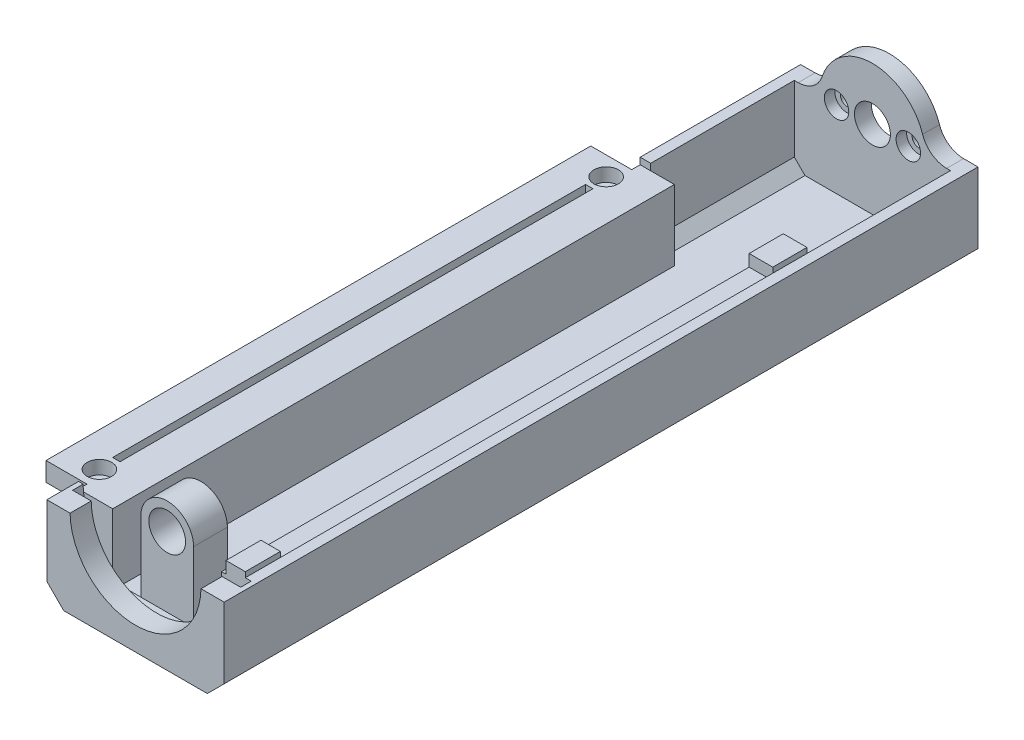
SolidWorks part; units mm, degrees
ref_plane "Front Plane" through (0, 0, 0) normal (0, 0, 1) x (1, 0, 0)
ref_plane "Top Plane" through (0, 0, 0) normal (0, 1, 0) x (1, 0, 0)
ref_plane "Right Plane" through (0, 0, 0) normal (1, 0, 0) x (0, 0, -1)
sketch "Sketch1" plane through (0, 0, 0) normal (0, 0, 1) x (1, 0, 0)
  line L0 (-21, -0.25) -> (21, -0.25)
  line L1 (-21, 21) -> (21, 21) construction
  line L2 (-21, 21) -> (-21, -21) construction
  line L3 (-21, -21) -> (21, -21) construction
  line L4 (21, 21) -> (21, -21) construction
  line L5 (-21, 21) -> (21, -21) construction
  line L6 (-21, -21) -> (21, 21) construction
  line L7 (21, -0.25) -> (21, -17)
  line L8 (21, -17) -> (17, -21)
  line L9 (17, -21) -> (-17, -21)
  line L10 (-17, -21) -> (-21, -17)
  line L11 (-21, -17) -> (-21, -0.25)
  point P0 (0, 0)
  dimension "D1" = 42
  dimension "D2" = 0.25
  dimension "D3" = 4
  dimension "D4" = 4
  dimension "D5" = 4
extrude "Boss-Extrude1" add sketch "Sketch1" along normal blind 178.5 contours L11 L0 L7 L8 L9 L10
ref_plane "Plane1" through (0, 0, 173.5) normal (0, 0, 1) x (1, 0, 0)
sketch "Sketch4" plane through (0, 0, 173.5) normal (0, 0, 1) x (1, 0, 0)
  line L6 (-18.5, -15.9645) -> (-15.9645, -18.5)
  line L7 (-15.9645, -18.5) -> (15.9645, -18.5)
  line L8 (15.9645, -18.5) -> (18.5, -15.9645)
  line L9 (18.5, -15.9645) -> (18.5, -2.75)
  line L11 (-18.5, -2.75) -> (-18.5, -15.9645)
  line L18 (-21, -17) -> (-17, -21)
  line L22 (-21, -0.25) -> (-21, -17)
  line L23 (21, -0.25) -> (-21, -0.25)
  line L24 (21, -17) -> (21, -0.25)
  line L25 (17, -21) -> (21, -17)
  line L26 (-17, -21) -> (17, -21)
  line L27 (-21, -17) -> (-17, -21) construction
  line L28 (-21, -0.25) -> (-21, -17) construction
  line L29 (21, -0.25) -> (-21, -0.25) construction
  line L30 (21, -17) -> (21, -0.25) construction
  line L31 (17, -21) -> (21, -17) construction
  line L32 (-17, -21) -> (17, -21) construction
  line L33 (-18.5, -2.75) -> (-18.5, -0.25)
  line L34 (-18.5, -0.25) -> (18.5, -0.25)
  line L35 (18.5, -0.25) -> (18.5, -2.75)
  line L39 (18.5, -2.75) -> (-18.5, -2.75) construction
  dimension "D1" = 0
  dimension "D2" = 2.5
extrude "Cut-Extrude3" cut sketch "Sketch4" against normal offset from surface (169.5 mm away) 4 up to face at (0, -12.75, 0)
sketch "Sketch3" plane through (0, 0, 178.5) normal (0, 0, 1) x (1, 0, 0)
  circle A0 centre (0, 0) radius 15.5
  dimension "D1" = 31
extrude "Cut-Extrude2" cut sketch "Sketch3" against normal up to next
sketch "Sketch6" plane through (0, 0, 173.5) normal (0, 0, 1) x (1, 0, 0)
  line L1 (-16.6, 16.6) -> (16.6, 16.6) construction
  line L2 (-16.6, 16.6) -> (-16.6, -16.6) construction
  line L3 (-16.6, -16.6) -> (16.6, -16.6) construction
  line L4 (16.6, 16.6) -> (16.6, -16.6) construction
  line L5 (-16.6, 16.6) -> (16.6, -16.6) construction
  line L6 (-16.6, -16.6) -> (16.6, 16.6) construction
  line L8 (-10.975, 16.6) -> (10.975, 16.6)
  line L9 (0, 0) -> (0, 16.6) construction
  line L20 (10.975, -16.6) -> (-10.975, -16.6)
  arc A13 (-10.975, 16.6) -> (-10.975, -16.6) centre (0, 0) ccw
  arc A14 (10.975, -16.6) -> (10.975, 16.6) centre (0, 0) ccw
  point P0 (0, 0)
  dimension "D1" = 39.8
  dimension "D2" = 33.2
extrude "Cut-Extrude4" cut sketch "Sketch6" against normal blind 2.5
ref_plane "Plane2" through (0, 0, 171) normal (0, 0, 1) x (1, 0, 0)
sketch "Sketch7" plane through (0, 0, 171) normal (0, 0, 1) x (1, 0, 0)
  line L1 (-6.25, 0) -> (-6.25, -21)
  line L2 (-6.25, -21) -> (6.25, -21)
  line L3 (6.25, -21) -> (6.25, 0)
  line L6 (17, -21) -> (-17, -21) construction
  arc A4 (-6.25, 0) -> (6.25, 0) centre (0, 0) cw
  circle A5 centre (0, 0) radius 4.25
  dimension "D2" = 6.25
  dimension "D1" = 8.5
extrude "Boss-Extrude3" add sketch "Sketch7" against normal blind 8 contours L3 A4 L1 L2
sketch "Sketch10" plane through (0, 0, 171) normal (0, 0, 1) x (1, 0, 0)
  line L0 (-18.5, -1.8) -> (-18.5, -15.9645)
  line L1 (-12.3089, -1.5) -> (-25.925, -1.5) construction
  line L2 (-18.5, -15.9645) -> (-15.9645, -18.5)
  line L3 (-15.9645, -18.5) -> (-12.9, -18.5)
  line L5 (-12.9, -18.5) -> (-12.9, -1.8)
  line L6 (-18.5, -1.8) -> (-12.9, -1.8)
  dimension "D1" = 0.3
  dimension "D2" = 0.5
extrude "Boss-Extrude4" add sketch "Sketch10" against normal blind 133 contours L6 L5 L3 L2 L0
mirror "Mirror1" about plane through (0, 0, 0) normal (1, 0, 0) of "Boss-Extrude4"
sketch "Sketch11" plane through (0, 0, 171) normal (0, 0, 1) x (1, 0, 0)
  circle A0 centre (0, 0) radius 4.35
  dimension "D1" = 8.7
extrude "Cut-Extrude6" cut sketch "Sketch11" against normal blind 10
sketch "Sketch12" plane through (0, 0, 38) normal (0, 0, -1) x (-1, 0, 0)
  line L1 (18.5, -1.8) -> (25.3381, -1.8)
  line L2 (18.5, -1.8) -> (18.5, 0)
  line L3 (18.5, 0) -> (25.3381, 0)
  line L4 (25.3381, -1.8) -> (25.3381, 0)
extrude "Cut-Extrude7" cut sketch "Sketch12" against normal up to vertex (133 mm away)
sketch "Sketch13" plane through (0, -1.8, 0) normal (0, 1, 0) x (1, 0, 0)
  line L0 (-18.5, -38) -> (-12.9, -38) construction
  line L1 (-12.9, -40) -> (-30.7, -40)
  line L2 (-12.9, -40) -> (-12.9, -169)
  line L3 (-12.9, -169) -> (-30.7, -169)
  line L4 (-30.7, -40) -> (-30.7, -169)
  line L5 (-12.9, -38) -> (-12.9, -171) construction
  dimension "D1" = 129
  dimension "D2" = 17.8
  dimension "D3" = 2
extrude "Boss-Extrude5" add sketch "Sketch13" against normal blind 4.5
sketch "Sketch16" plane through (0, -6.3, 0) normal (0, -1, 0) x (1, 0, 0)
  line L2 (-30.7, 169) -> (-21, 169) construction
  line L3 (-30.7, 40) -> (-14.4, 40)
  line L4 (-30.7, 40) -> (-30.7, 169)
  line L5 (-30.7, 169) -> (-14.4, 169)
  line L6 (-14.4, 40) -> (-14.4, 169)
  dimension "D1" = 16.3
extrude "Cut-Extrude8" cut sketch "Sketch16" along normal through all
sketch "Sketch17" plane through (0, -6.3, 0) normal (0, -1, 0) x (1, 0, 0)
  line L0 (-22.55, 40) -> (-22.55, 169) construction
  line L1 (-30.7, 40) -> (-14.4, 40) construction
  line L2 (-30.7, 169) -> (-21, 169) construction
  line L3 (-22.55, 104.5) -> (-30.7, 104.5) construction
  line L4 (-21.675, 48.5) -> (-23.425, 48.5)
  line L5 (-21.675, 48.5) -> (-21.675, 160.5)
  line L6 (-21.675, 160.5) -> (-23.425, 160.5)
  line L7 (-23.425, 48.5) -> (-23.425, 160.5)
  line L8 (-21.675, 48.5) -> (-23.425, 160.5) construction
  line L9 (-21.675, 160.5) -> (-23.425, 48.5) construction
  line L10 (-30.7, 40) -> (-30.7, 169) construction
  circle A0 centre (-22.55, 164.5) radius 1.6
  circle A1 centre (-22.55, 44.5) radius 1.6
  point P7 (-22.55, 104.5)
  point P8 (-22.55, 40)
  dimension "D3" = 3.2
  dimension "D1" = 112
  dimension "D2" = 1.75
  dimension "D4" = 60
extrude "Cut-Extrude10" cut sketch "Sketch17" against normal through all
sketch "Sketch18" plane through (0, -1.8, 0) normal (0, 1, 0) x (1, 0, 0)
  circle A0 centre (-22.55, -164.5) radius 2.9
  circle A1 centre (-22.55, -44.5) radius 2.9
  dimension "D1" = 5.8
extrude "Cut-Extrude11" cut sketch "Sketch18" against normal blind 3.2
sketch "Sketch19" plane through (0, 0, 0) normal (0, 0, 1) x (1, 0, 0)
  circle A0 centre (0, 0) radius 12.5
  dimension "D1" = 25
extrude "Boss-Extrude6" add sketch "Sketch19" along normal blind 4 contours A0
sketch "Sketch20" plane through (0, 0, 0) normal (0, 0, 1) x (1, 0, 0)
  line L0 (-21, 21) -> (21, -21) construction
  line L1 (-21, -0.25) -> (21, -0.25) construction
  line L2 (0, 0) -> (0, 12.5) construction
  circle A0 centre (0, 0) radius 4.25
  circle A1 centre (-8.5, -0.25) radius 1.6
  arc A2 (12.4975, -0.25) -> (-12.4975, -0.25) centre (0, 0) ccw construction
  circle A3 centre (8.5, -0.25) radius 1.6
  dimension "D1" = 8.5
  dimension "D2" = 3.2
  dimension "D3" = 8.5
extrude "Cut-Extrude12" cut sketch "Sketch20" along normal blind 4
sketch "Sketch21" plane through (0, 0, 4) normal (0, 0, 1) x (1, 0, 0)
  circle A0 centre (-8.5, -0.25) radius 2.9
  circle A1 centre (8.5, -0.25) radius 2.9
  dimension "D1" = 5.8
extrude "Cut-Extrude13" cut sketch "Sketch21" against normal blind 2.5
fillet "Fillet1" radius 6 2 edges at (12.4975, -0.25, 2) (-12.4975, -0.25, 2)
sketch "Sketch22" plane through (0, -1.8, 0) normal (0, 1, 0) x (1, 0, 0)
  line L0 (18.5, -38) -> (18.5, -171) construction
  line L1 (12.9, -38) -> (18.5, -38)
  line L2 (12.9, -38) -> (12.9, -46.1)
  line L3 (12.9, -46.1) -> (18.5, -46.1)
  line L4 (18.5, -38) -> (18.5, -46.1)
  line L5 (18.5, -171) -> (12.9, -171) construction
  line L6 (18.5, -171) -> (13.9, -171)
  line L7 (18.5, -171) -> (18.5, -162.7)
  line L8 (18.5, -162.7) -> (13.9, -162.7)
  line L9 (13.9, -171) -> (13.9, -162.7)
  line L10 (12.9, -38) -> (12.9, -171) construction
  point P13 (14.3699, -171)
  point P14 (18.5, -171)
  dimension "D1" = 8.1
  dimension "D2" = 1
  dimension "D3" = 8.3
extrude "Boss-Extrude7" add sketch "Sketch22" along normal blind 2.8
sketch "Sketch23" plane through (0, 0, 173.5) normal (0, 0, -1) x (-1, 0, 0)
  line L0 (-10.975, -16.6) -> (10.975, -16.6) construction
  line L1 (-10.975, -16.6) -> (10.975, -16.6)
  line L2 (18.5, -7.3321) -> (-18.5, -7.3321) construction
  line L4 (-18.5, -15.9645) -> (-18.5, -7.3321) construction
  line L5 (-15.9645, -18.5) -> (-18.5, -15.9645) construction
  line L6 (15.9645, -18.5) -> (-15.9645, -18.5) construction
  line L7 (18.5, -15.9645) -> (15.9645, -18.5) construction
  line L8 (18.5, -7.3321) -> (18.5, -15.9645) construction
  line L9 (-18.5, -15.9645) -> (-18.5, -7.3321)
  line L10 (-15.9645, -18.5) -> (-18.5, -15.9645)
  line L11 (15.9645, -18.5) -> (-15.9645, -18.5)
  line L12 (18.5, -15.9645) -> (15.9645, -18.5)
  line L13 (18.5, -7.3321) -> (18.5, -15.9645)
  arc A0 (-10.975, 16.6) -> (-10.975, -16.6) centre (0, 0) ccw construction
  arc A1 (10.975, -16.6) -> (10.975, 16.6) centre (0, 0) ccw construction
  arc A2 (-18.5, -7.3321) -> (-10.975, -16.6) centre (0, 0) ccw
  arc A3 (10.975, -16.6) -> (18.5, -7.3321) centre (0, 0) ccw
  point P4 (0, 0)
  point P6 (10.975, -16.6)
  point P8 (0, 0)
  point P11 (18.5, -5.5183)
  point P14 (0, 0)
extrude "Boss-Extrude8" add sketch "Sketch23" along normal up to surface (2.5 mm away)
